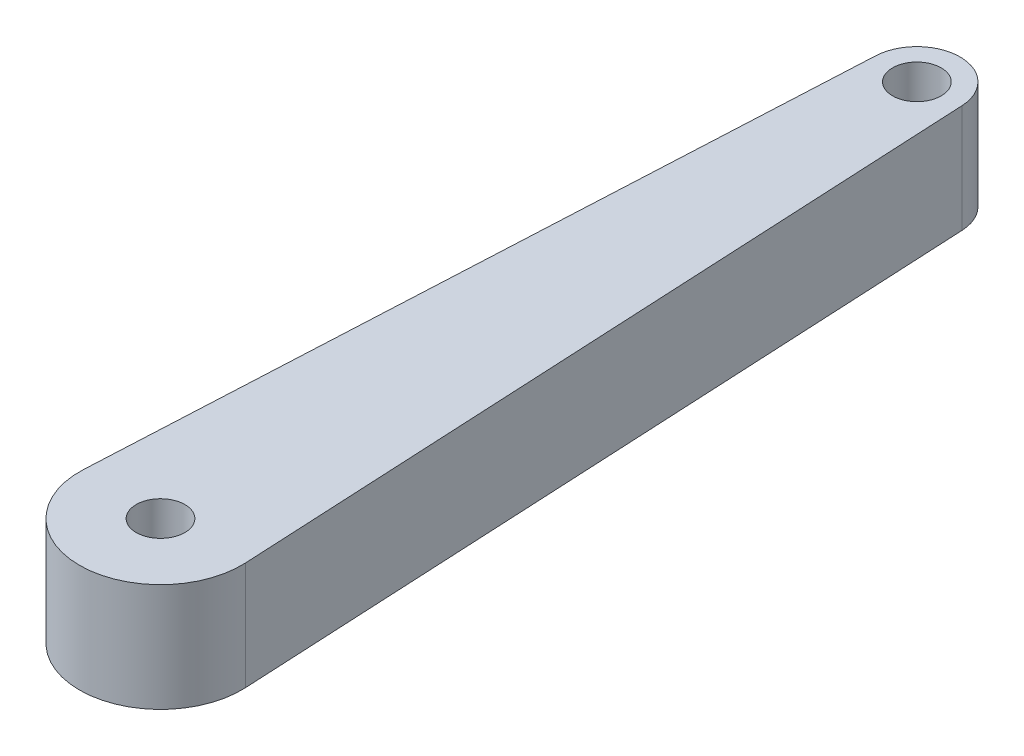
SolidWorks part; units mm, degrees
ref_plane "Front Plane" through (0, 0, 0) normal (0, 0, 1) x (1, 0, 0)
ref_plane "Top Plane" through (0, 0, 0) normal (0, 1, 0) x (1, 0, 0)
ref_plane "Right Plane" through (0, 0, 0) normal (1, 0, 0) x (0, 0, -1)
sketch "Sketch1" plane through (0, 0, 0) normal (0, 1, 0) x (1, 0, 0)
  line L0 (0, 0) -> (0, 35) construction
  line L1 (-3.7453, 0.1875) -> (-1.9975, 35.1)
  line L2 (3.7453, 0.1875) -> (1.9975, 35.1)
  circle A0 centre (0, 35) radius 2
  circle A1 centre (0, 0) radius 3.75
  circle A2 centre (0, 35) radius 1.125
  circle A3 centre (0, 0) radius 1.125
  dimension "D1" = 4
  dimension "D2" = 7.5
  dimension "D4" = 2.25
  dimension "D5" = 2.25
  dimension "D3" = 35
extrude "Boss-Extrude1" add sketch "Sketch1" along normal blind 5
